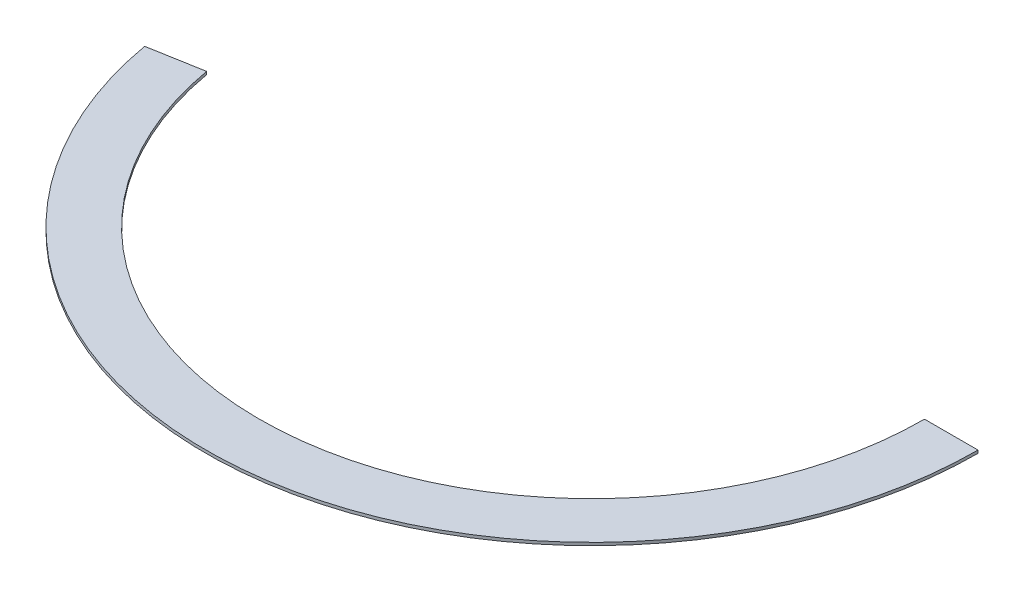
SolidWorks part; units mm, degrees
ref_plane "Front Plane" through (0, 0, 0) normal (0, 0, 1) x (1, 0, 0)
ref_plane "Top Plane" through (0, 0, 0) normal (0, 1, 0) x (1, 0, 0)
ref_plane "Right Plane" through (0, 0, 0) normal (1, 0, 0) x (0, 0, -1)
sketch "Sketch3" plane through (0, 0, 0) normal (0, 1, 0) x (1, 0, 0)
  line L0 (-79.602, -14.036) -> (-92.4045, -16.2934)
  line L1 (80.83, 0) -> (93.83, 0)
  arc A0 (-92.4045, -16.2934) -> (93.83, 0) centre (0, 0) ccw
  arc A1 (80.83, 0) -> (-79.602, -14.036) centre (0, 0) cw
  dimension "D1" = 13
  dimension "D2" = 93.83
  dimension "D3" = 190
extrude "Boss-Extrude1" add sketch "Sketch3" along normal blind 0.7
